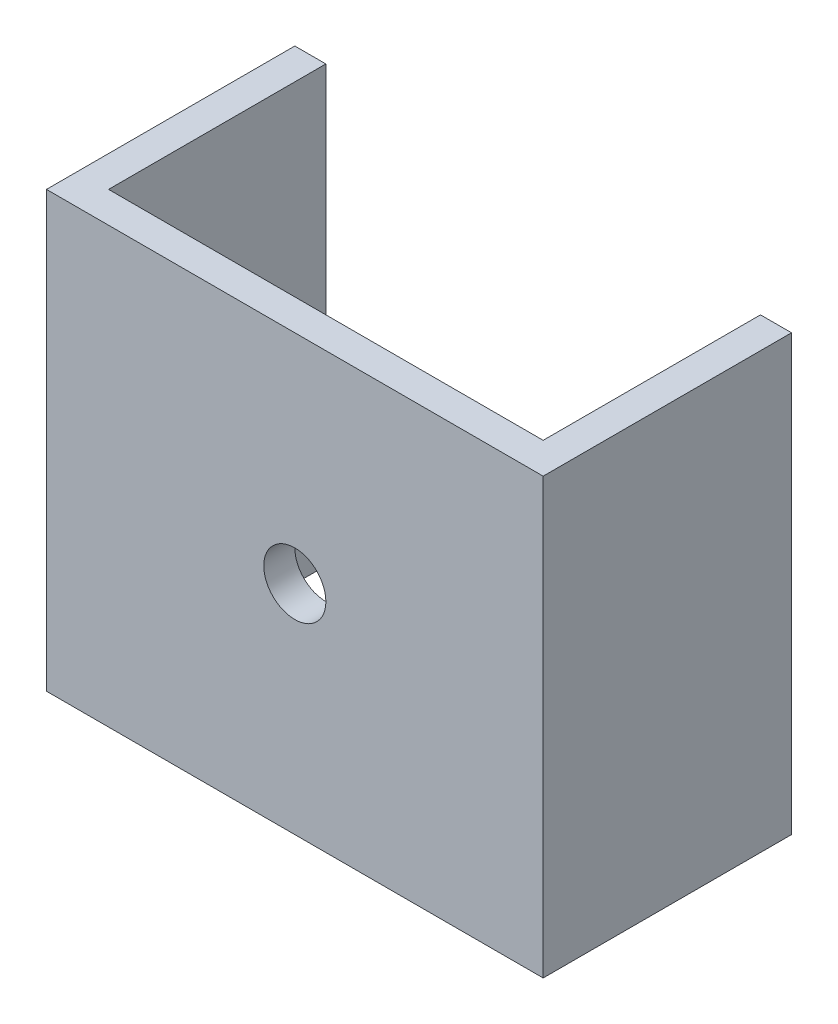
SolidWorks part; units mm, degrees
ref_plane "Front Plane" through (0, 0, 0) normal (0, 0, 1) x (1, 0, 0)
ref_plane "Top Plane" through (0, 0, 0) normal (0, 1, 0) x (1, 0, 0)
ref_plane "Right Plane" through (0, 0, 0) normal (1, 0, 0) x (0, 0, -1)
sketch "Sketch1" plane through (0, 0, 0) normal (0, 1, 0) x (1, 0, 0)
  line L0 (47.625, 25.4) -> (50.8, 25.4)
  line L1 (0, 0) -> (50.8, 0)
  line L2 (0, 0) -> (0, 25.4)
  line L3 (0, 25.4) -> (3.175, 25.4)
  line L4 (50.8, 0) -> (50.8, 25.4)
  line L6 (3.175, 25.4) -> (3.175, 3.175)
  line L7 (3.175, 3.175) -> (47.625, 3.175)
  line L8 (47.625, 25.4) -> (47.625, 3.175)
  dimension "D1" = 50.8
  dimension "D2" = 25.4
  dimension "D3" = 3.175
  dimension "D4" = 3.175
  dimension "D5" = 3.175
extrude "Boss-Extrude1" add sketch "Sketch1" along normal blind 44.45
sketch "Sketch2" plane through (0, 0, 0) normal (0, 0, 1) x (1, 0, 0)
  line L0 (-1000, 22.225) -> (49000, 22.225) construction
  line L1 (0, 44.45) -> (0, 0) construction
  line L2 (25.4, -1000) -> (25.4, 49000) construction
  line L3 (0, 0) -> (50.8, 0) construction
  circle A0 centre (25.4, 22.225) radius 3.175
  point P5 (0, 22.225)
  point P10 (25.4, 0)
  dimension "D1" = 6.35
extrude "Cut-Extrude1" cut sketch "Sketch2" against normal through all
